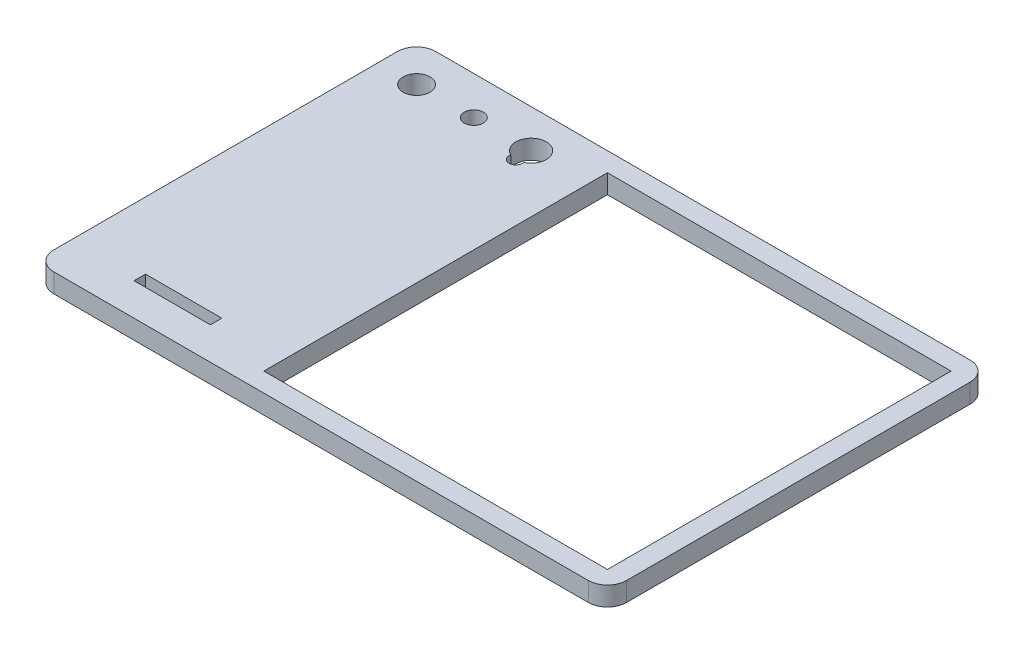
SolidWorks part; units mm, degrees
ref_plane "Front Plane" through (0, 0, 0) normal (0, 0, 1) x (1, 0, 0)
ref_plane "Top Plane" through (0, 0, 0) normal (0, 1, 0) x (1, 0, 0)
ref_plane "Right Plane" through (0, 0, 0) normal (1, 0, 0) x (0, 0, -1)
sketch "Sketch1" plane through (0, 0, 0) normal (0, 1, 0) x (1, 0, 0)
  line L0 (70, 50) -> (70, -50) construction
  line L1 (-75, -50) -> (75, -50)
  line L2 (-75, -50) -> (-75, 50)
  line L3 (-75, 50) -> (75, 50)
  line L4 (75, -50) -> (75, 50)
  line L5 (-75, -50) -> (75, 50) construction
  line L6 (-75, 50) -> (75, -50) construction
  line L7 (75, 45) -> (-75, 45) construction
  line L8 (75, -45) -> (-75, -45) construction
  line L14 (70, 45) -> (-20, 45)
  line L15 (70, 45) -> (70, -45)
  line L16 (70, -45) -> (-20, -45)
  line L17 (-20, 45) -> (-20, -45)
  point P0 (0, 0)
  dimension "D1" = 150
  dimension "D2" = 100
  dimension "D3" = 5
  dimension "D4" = 5
  dimension "D5" = 5
  dimension "D6" = 90
  dimension "D7" = 90
extrude "Boss-Extrude1" add sketch "Sketch1" along normal blind 5
fillet "Fillet1" radius 5 4 edges at (75, 2.5, -50) (-75, 2.5, -50) (-75, 2.5, 50) (75, 2.5, 50)
ref_plane "Plane1" through (0, 5, 0) normal (0, 1, 0) x (1, 0, 0)
sketch "Sketch2" plane through (0, 5, 0) normal (0, 1, 0) x (1, 0, 0)
  line L0 (-20, 45) -> (-20, -50)
  line L1 (-70, -50) -> (70, -50) construction
  line L2 (70, 50) -> (-70, 50) construction
  line L3 (-20, 50) -> (-75, 50)
  line L4 (-20, 50) -> (-20, -50)
  line L5 (-20, -50) -> (-75, -50)
  line L6 (-75, 50) -> (-75, -50)
  line L7 (-75, 45) -> (-75, -45) construction
  line L8 (-75, 40) -> (-20, 40) construction
  line L9 (-65, 50) -> (-65, 40) construction
  line L10 (-50, 50) -> (-50, 40) construction
  line L11 (-35, 50) -> (-35, 40) construction
  line L12 (-35, 36) -> (-20, 36) construction
  line L13 (-75, -40) -> (-20, -40) construction
  line L15 (-47.5, -50) -> (-47.5, -40) construction
  line L18 (-57.5, -41.5) -> (-37.5, -41.5)
  line L19 (-57.5, -41.5) -> (-57.5, -38.5)
  line L20 (-57.5, -38.5) -> (-37.5, -38.5)
  line L21 (-37.5, -41.5) -> (-37.5, -38.5)
  line L22 (-57.5, -41.5) -> (-37.5, -38.5) construction
  line L23 (-57.5, -38.5) -> (-37.5, -41.5) construction
  circle A0 centre (-65, 40) radius 3.5
  circle A1 centre (-50, 40) radius 2.5
  circle A2 centre (-35, 40) radius 4
  circle A3 centre (-35, 36) radius 1.75
  dimension "D6" = 7
  dimension "D7" = 5
  dimension "D8" = 8
  dimension "D9" = 3.5
  dimension "D1" = 100
  dimension "D2" = 10
  dimension "D3" = 10
  dimension "D4" = 25
  dimension "D5" = 40
  dimension "D10" = 10
  dimension "D11" = 20
  dimension "D12" = 3
extrude "Cut-Extrude3" cut sketch "Sketch2" against normal blind 5 contours A0 | A1 | A3 A2 | A2 A3 | A2 A3 | L18 L21 L20 L19
